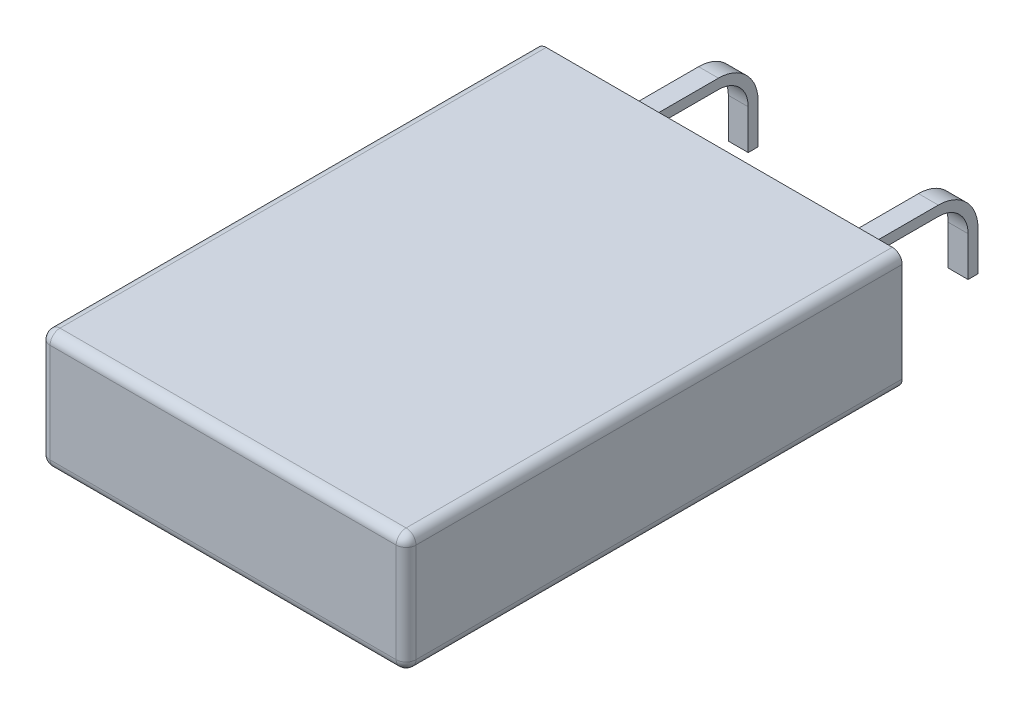
SolidWorks part; units mm, degrees
material "Chrome Stainless Steel"
ref_plane "Front" through (0, 0, 0) normal (0, 0, 1) x (1, 0, 0)
ref_plane "Top" through (0, 0, 0) normal (0, 1, 0) x (1, 0, 0)
ref_plane "Right" through (0, 0, 0) normal (1, 0, 0) x (0, 0, -1)
other "Configuration Table"
sketch "Sketch2" plane through (0, 0, 0) normal (0, 0, 1) x (1, 0, 0)
  line L1 (0.5, 0) -> (17.94, 0)
  line L2 (0, 0.5) -> (0, 5.5)
  line L3 (0.5, 6) -> (17.94, 6)
  line L4 (18.44, 0.5) -> (18.44, 5.5)
  arc A0 (17.94, 6) -> (18.44, 5.5) centre (17.94, 5.5) cw
  arc A1 (17.94, 0) -> (18.44, 0.5) centre (17.94, 0.5) ccw
  arc A2 (0, 5.5) -> (0.5, 6) centre (0.5, 5.5) cw
  arc A3 (0.5, 0) -> (0, 0.5) centre (0.5, 0.5) cw
  point P6 (18.44, 6)
  point P9 (18.44, 0)
  point P12 (0, 6)
  point P15 (0, 0)
  dimension "D3" = 0.5
  dimension "D1" = 18.44
  dimension "D2" = 6
extrude "Extrude1" add sketch "Sketch2" against normal blind 25
fillet "Fillet1" radius 0.5 8 edges at (18.2936, 5.8536, 0) (18.44, 3, 0) (18.2936, 0.1464, 0) (9.22, 0, 0) (0.1464, 0.1464, 0) (0, 3, 0) (0.1464, 5.8536, 0) (9.22, 6, 0)
sketch "Sketch3" plane through (0, 0, -25) normal (0, 0, -1) x (-1, 0, 0)
  line L8 (-17.44, 5) -> (-17.44, 1)
  line L9 (-17.44, 1) -> (-1, 1)
  line L10 (-1, 1) -> (-1, 5)
  line L11 (-1, 5) -> (-17.44, 5)
  line L12 (-17.44, 5) -> (-17.44, 1)
  line L13 (-17.44, 1) -> (-1, 1)
  line L14 (-1, 1) -> (-1, 5)
  line L15 (-1, 5) -> (-17.44, 5)
  dimension "D1" = 1
extrude "Cut-Extrude1" cut sketch "Sketch3" against normal blind 5
sketch "Profile" plane through (0, 0, -20) normal (0, 0, -1) x (-1, 0, 0)
  line L0 (-0.5, 0) -> (-17.94, 0) construction
  line L1 (-15.26, 4) -> (-14.26, 4)
  line L2 (-15.26, 4) -> (-15.26, 3.5)
  line L3 (-15.26, 3.5) -> (-14.26, 3.5)
  line L4 (-14.26, 4) -> (-14.26, 3.5)
  line L5 (-18.44, 0.5) -> (-18.44, 5.5) construction
  line L6 (-9.22, 6) -> (-9.22, 0) construction
  line L7 (-17.94, 6) -> (-0.5, 6) construction
  line L8 (-4.18, 4) -> (-4.18, 3.5)
  line L9 (-3.18, 3.5) -> (-4.18, 3.5)
  line L10 (-3.18, 4) -> (-3.18, 3.5)
  line L11 (-3.18, 4) -> (-4.18, 4)
  dimension "D1" = 1
  dimension "D2" = 0.5
  dimension "D3" = 4
  dimension "D4" = 3.18
ref_plane "Plane2" through (9.22, 0, 0) normal (1, 0, 0) x (0, 0, -1)
sketch "Path" plane through (9.22, 0, 0) normal (1, 0, 0) x (0, 0, -1)
  line L0 (20, 3.5) -> (30, 3.5)
  line L1 (20, 4) -> (20, 3.5) construction
  line L2 (31.5, 2) -> (31.5, 0)
  arc A0 (30, 3.5) -> (31.5, 2) centre (30, 2) cw
  point P8 (31.5, 3.5)
  dimension "D3" = 1.5
  dimension "D1" = 11.5
sweep "Sweep1" add profiles "Profile" path "Path"
